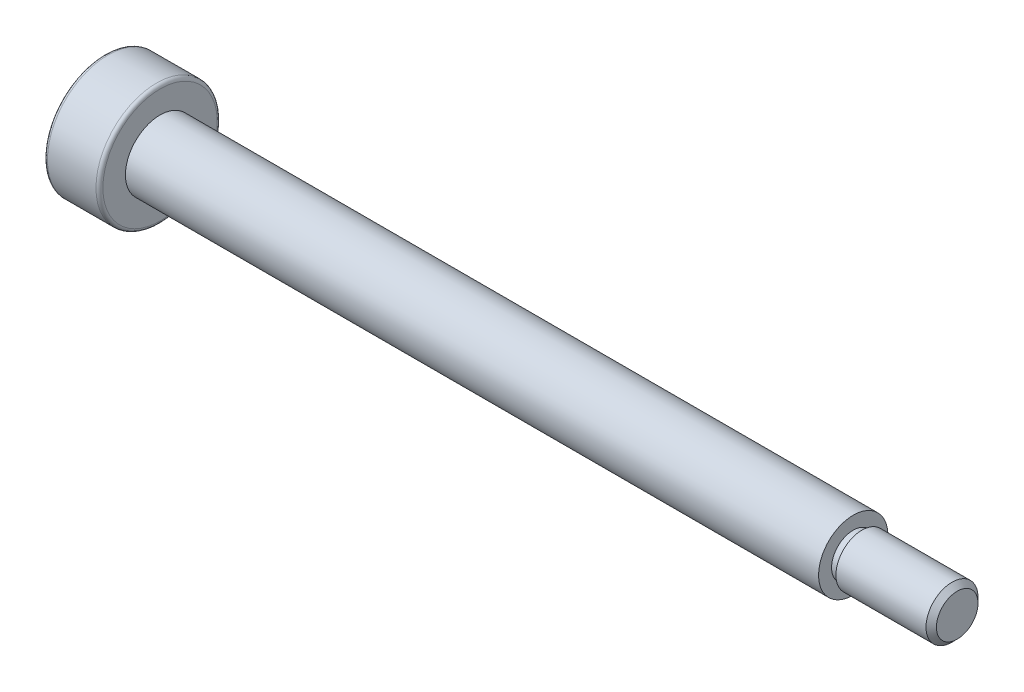
SolidWorks part; units mm, degrees
ref_plane "前视基准面" through (0, 0, 0) normal (0, 0, 1) x (1, 0, 0)
ref_plane "上视基准面" through (0, 0, 0) normal (0, 1, 0) x (1, 0, 0)
ref_plane "右视基准面" through (0, 0, 0) normal (1, 0, 0) x (0, 0, -1)
sketch "草图1" plane through (0, 0, 0) normal (0, 0, 1) x (1, 0, 0)
  line L0 (-24.6, 0) -> (24.6, 0) construction
  line L1 (-24.6, 0) -> (-24.6, 3.5)
  line L2 (-24.6, 3.5) -> (-21.4, 3.5)
  line L3 (-21.4, 3.5) -> (-21.4, 2)
  line L4 (-21.4, 2) -> (18.6, 2)
  line L5 (18.6, 2) -> (18.6, 1.5)
  line L6 (18.6, 1.5) -> (24.6, 1.5)
  line L7 (24.6, 1.5) -> (24.6, 0)
  line L8 (-24.6, 0) -> (24.6, 0)
  dimension "D1" = 4
  dimension "D2" = 7
  dimension "D3" = 3
  dimension "D4" = 6
  dimension "D5" = 40
  dimension "D6" = 3.2
revolve "旋转1" add sketch "草图1" angle 360 about L0
fillet "圆角1" radius 0.2 2 edges at (-21.4, 0, 3.5) (-24.6, 0, 3.5)
chamfer "倒角1" distance 0.3 angle 45 1 edges at (24.6, 0, 1.5)
sketch "草图3" plane through (0, 0, 0) normal (0, 0, 1) x (1, 0, 0)
  line L0 (18.6, 0) -> (24.3, 0) construction
  line L1 (18.6, -1.5) -> (18.6, 1.5) construction
  line L2 (24.3, 1.5) -> (24.3, -1.5) construction
  line L3 (18.6, -2) -> (18.6, 2) construction
  line L4 (18.6, 1.5) -> (19.1, 1.5)
  line L5 (18.6, 1.5) -> (18.6, 1.25)
  line L6 (18.6, 1.25) -> (19.1, 1.25)
  line L7 (19.1, 1.5) -> (19.1, 1.25)
  line L8 (24.3, 1.5) -> (18.6, 1.5) construction
  dimension "D1" = 2.5
  dimension "D2" = 0.5
revolve "切除-旋转1" cut sketch "草图3" angle 360 about L0
sketch "草图4" plane through (-24.6, 0, 0) normal (-1, 0, 0) x (0, 0, 1)
  line L1 (1.7321, 0) -> (0.866, 1.5)
  line L2 (0.866, 1.5) -> (-0.866, 1.5)
  line L3 (-0.866, 1.5) -> (-1.7321, 0)
  line L4 (-1.7321, 0) -> (-0.866, -1.5)
  line L5 (-0.866, -1.5) -> (0.866, -1.5)
  line L6 (0.866, -1.5) -> (1.7321, 0)
  circle A0 centre (0, 0) radius 1.5 construction
  dimension "D1" = 3
extrude "切除-拉伸1" cut sketch "草图4" against normal blind 2
